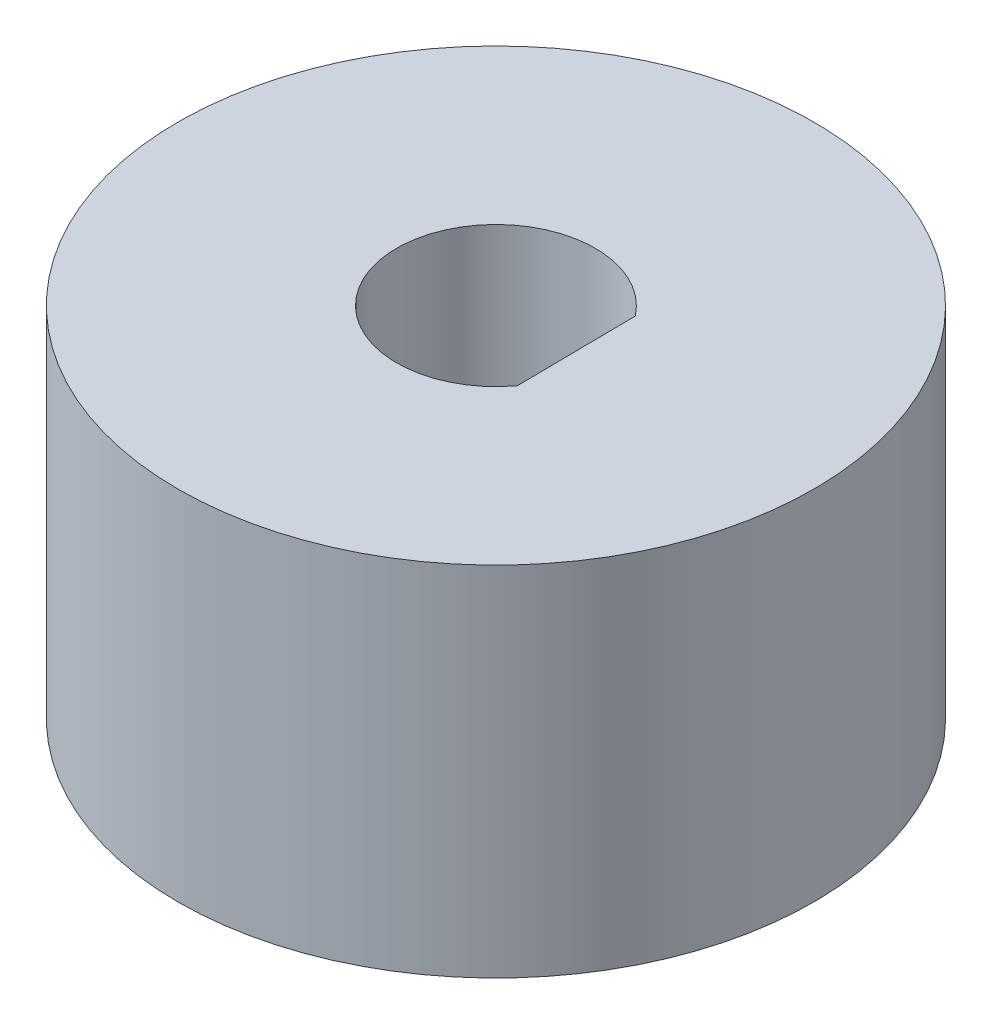
SolidWorks part; units mm, degrees
ref_plane "前视基准面" through (0, 0, 0) normal (0, 0, 1) x (1, 0, 0)
ref_plane "上视基准面" through (0, 0, 0) normal (0, 1, 0) x (1, 0, 0)
ref_plane "右视基准面" through (0, 0, 0) normal (1, 0, 0) x (0, 0, -1)
sketch "草图1" plane through (0, 0, 0) normal (0, 1, 0) x (1, 0, 0)
  circle A0 centre (0, 0) radius 8
  dimension "D1" = 16
extrude "凸台-拉伸1" add sketch "草图1" along normal blind 9
sketch "草图2" plane through (0, 9, 0) normal (0, 1, 0) x (1, 0, 0)
  line L0 (1.9825, 1.523) -> (2.0172, -1.4768)
  arc A1 (2.0172, -1.4768) -> (1.9825, 1.523) centre (0, 0) cw
  dimension "D1" = 2
  dimension "D2" = 2.5
extrude "切除-拉伸1" cut sketch "草图2" against normal through all
